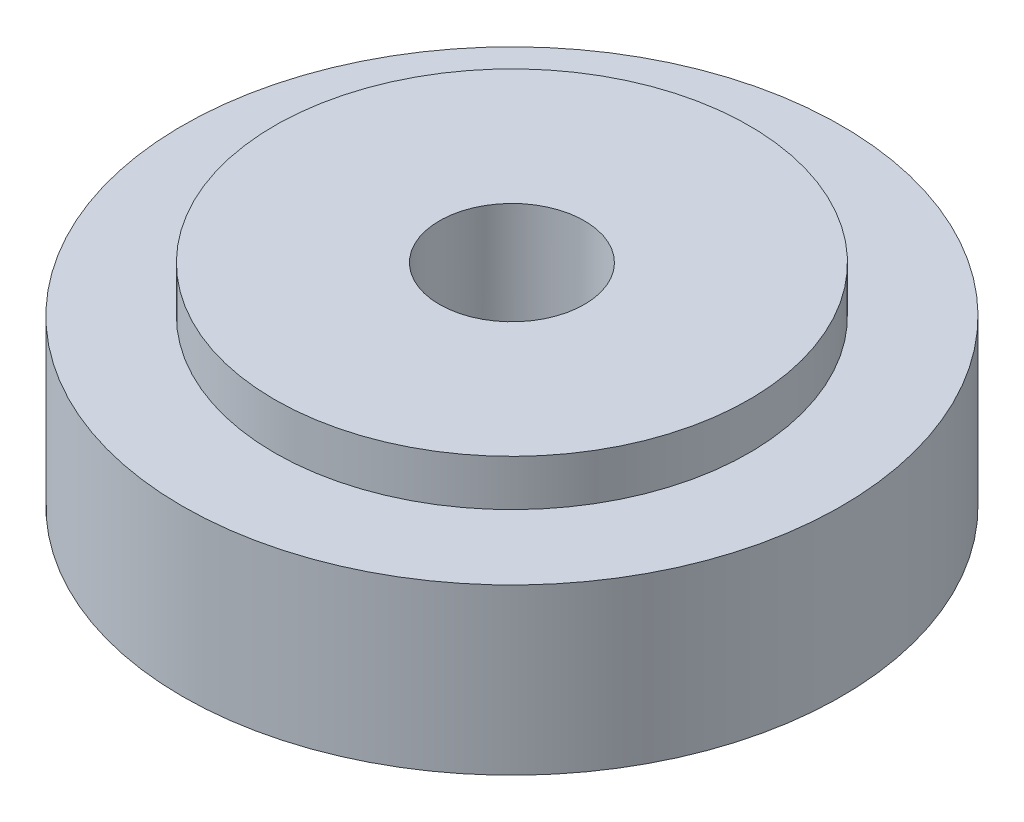
SolidWorks part; units mm, degrees
ref_plane "前视基准面" through (0, 0, 0) normal (0, 0, 1) x (1, 0, 0)
ref_plane "上视基准面" through (0, 0, 0) normal (0, 1, 0) x (1, 0, 0)
ref_plane "右视基准面" through (0, 0, 0) normal (1, 0, 0) x (0, 0, -1)
other "Configuration Table"
sketch "草图1" plane through (0, 0, 0) normal (0, 1, 0) x (1, 0, 0)
  circle A0 centre (0, 0) radius 5
  dimension "D1" = 10
extrude "凸台-拉伸1" add sketch "草图1" along normal blind 2.5
sketch "草图2" plane through (0, 2.5, 0) normal (0, 1, 0) x (1, 0, 0)
  circle A0 centre (0, 0) radius 3.6
  dimension "D1" = 7.2
extrude "凸台-拉伸2" add sketch "草图2" along normal blind 0.7
sketch "草图3" plane through (0, 3.2, 0) normal (0, 1, 0) x (1, 0, 0)
  circle A0 centre (0, 0) radius 1.1
  dimension "D1" = 2.2
extrude "切除-拉伸1" cut sketch "草图3" against normal through all
sketch "草图4" plane through (0, 0, 0) normal (0, -1, 0) x (1, 0, 0)
  circle A0 centre (0, 0) radius 1.9
  dimension "D1" = 3.8
extrude "切除-拉伸2" cut sketch "草图4" against normal blind 1
